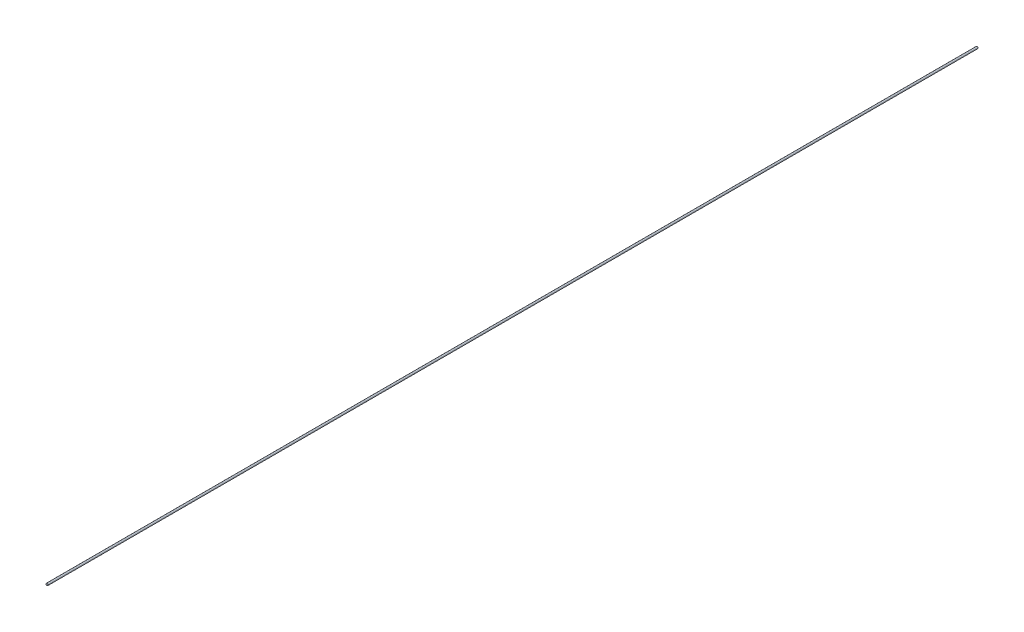
SolidWorks part; units mm, degrees
material "AISI 1015 Aço, trefilado (SS)"
ref_plane "Plano frontal" through (0, 0, 0) normal (0, 0, 1) x (1, 0, 0)
ref_plane "Plano superior" through (0, 0, 0) normal (0, 1, 0) x (1, 0, 0)
ref_plane "Plano direito" through (0, 0, 0) normal (1, 0, 0) x (0, 0, -1)
sketch "Esboço1" plane through (0, 0, 0) normal (0, 0, 1) x (1, 0, 0)
  circle A0 centre (0, 0) radius 5
  dimension "D1" = 10
extrude "Ressalto-extrusão1" add sketch "Esboço1" along normal mid plane 4740 contours A0
